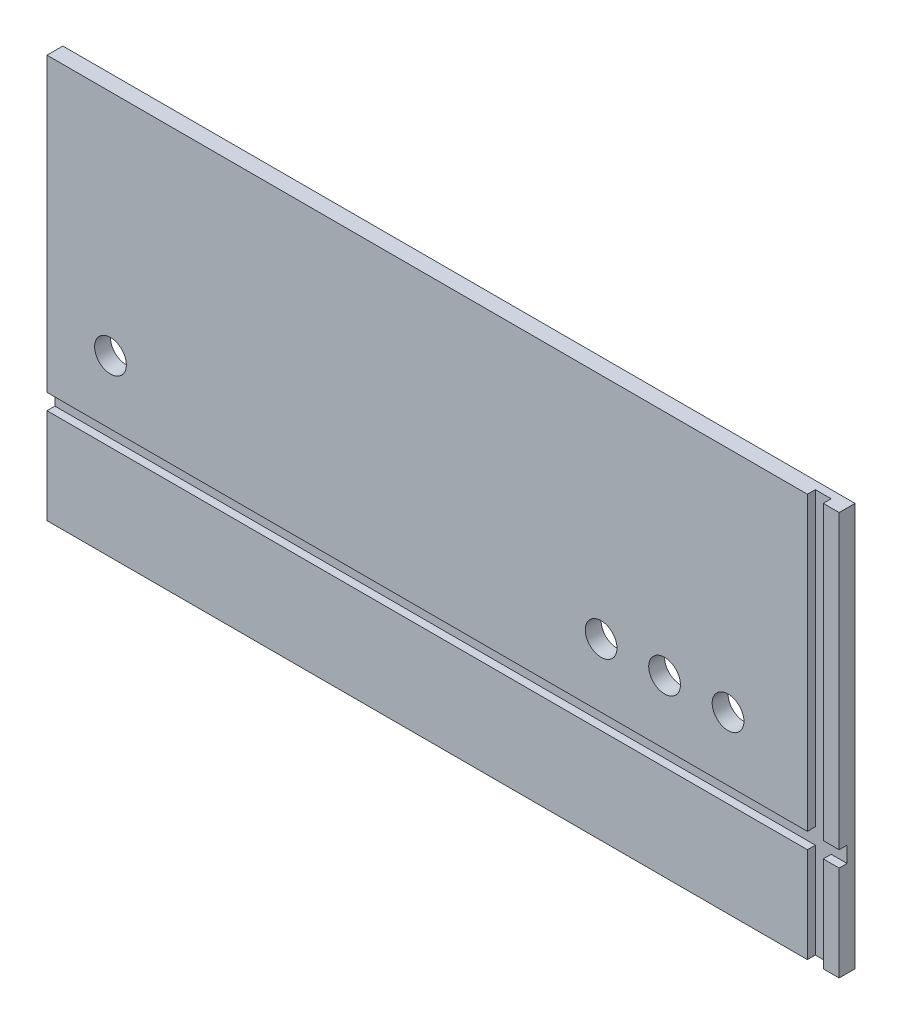
SolidWorks part; units mm, degrees
ref_plane "Front Plane" through (0, 0, 0) normal (0, 0, 1) x (1, 0, 0)
ref_plane "Top Plane" through (0, 0, 0) normal (0, 1, 0) x (1, 0, 0)
ref_plane "Right Plane" through (0, 0, 0) normal (1, 0, 0) x (0, 0, -1)
sketch "Sketch1" plane through (0, 0, 0) normal (0, 0, 1) x (1, 0, 0)
  line L0 (89.265, 0) -> (148.955, 0)
  line L1 (89.265, 0) -> (0, 0)
  line L2 (0, 0) -> (0, 80.645)
  line L3 (0, 80.645) -> (148.955, 80.645)
  line L4 (148.955, 80.645) -> (148.955, 0)
extrude "Boss-Extrude1" add sketch "Sketch1" along normal blind 3.175
sketch "Sketch2" plane through (148.955, 0, 0) normal (1, 0, 0) x (0, 0, -1)
  line L1 (-3.175, 0) -> (-3.175, 80.645) construction
  line L2 (-3.175, 19.05) -> (-3.175, 22.225)
  line L3 (-3.175, 22.225) -> (-1.5875, 22.225)
  line L4 (-1.5875, 22.225) -> (-1.5875, 19.05)
  line L5 (-1.5875, 19.05) -> (-3.175, 19.05)
extrude "Cut-Extrude1" cut sketch "Sketch2" against normal through all
sketch "Sketch3" plane through (0, 0, 3.175) normal (0, 0, 1) x (1, 0, 0)
  circle A0 centre (12.7, 34.925) radius 3.175
  circle A1 centre (136.255, 34.925) radius 3.175
  circle A2 centre (123.555, 34.925) radius 3.175
  circle A3 centre (110.855, 34.925) radius 3.175
  dimension "D1" = 3
extrude "Cut-Extrude2" cut sketch "Sketch3" against normal through all
sketch "Sketch4" plane through (148.955, 0, 0) normal (1, 0, 0) x (0, 0, -1)
  line L0 (-3.175, 19.05) -> (-3.175, 0)
  line L1 (-3.175, 80.645) -> (0, 80.645)
  line L2 (-3.175, 80.645) -> (-3.175, 22.225)
  line L3 (-3.175, 0) -> (0, 0)
  line L4 (0, 80.645) -> (0, 0)
  line L5 (-1.5875, 22.225) -> (-3.175, 22.225)
  line L6 (-1.5875, 22.225) -> (-1.5875, 19.05)
  line L7 (-1.5875, 19.05) -> (-3.175, 19.05)
extrude "Boss-Extrude2" add sketch "Sketch4" along normal blind 9.525
sketch "Sketch5" plane through (0, 0, 3.175) normal (0, 0, 1) x (1, 0, 0)
  line L1 (158.48, 80.645) -> (0, 80.645) construction
  line L2 (155.305, 80.645) -> (155.305, 0)
  line L3 (0, 0) -> (158.48, 0) construction
  line L4 (155.305, 0) -> (152.13, 0)
  line L5 (152.13, 80.645) -> (152.13, 0)
  line L6 (152.13, 80.645) -> (155.305, 80.645)
extrude "Cut-Extrude3" cut sketch "Sketch5" against normal blind 1.5875
